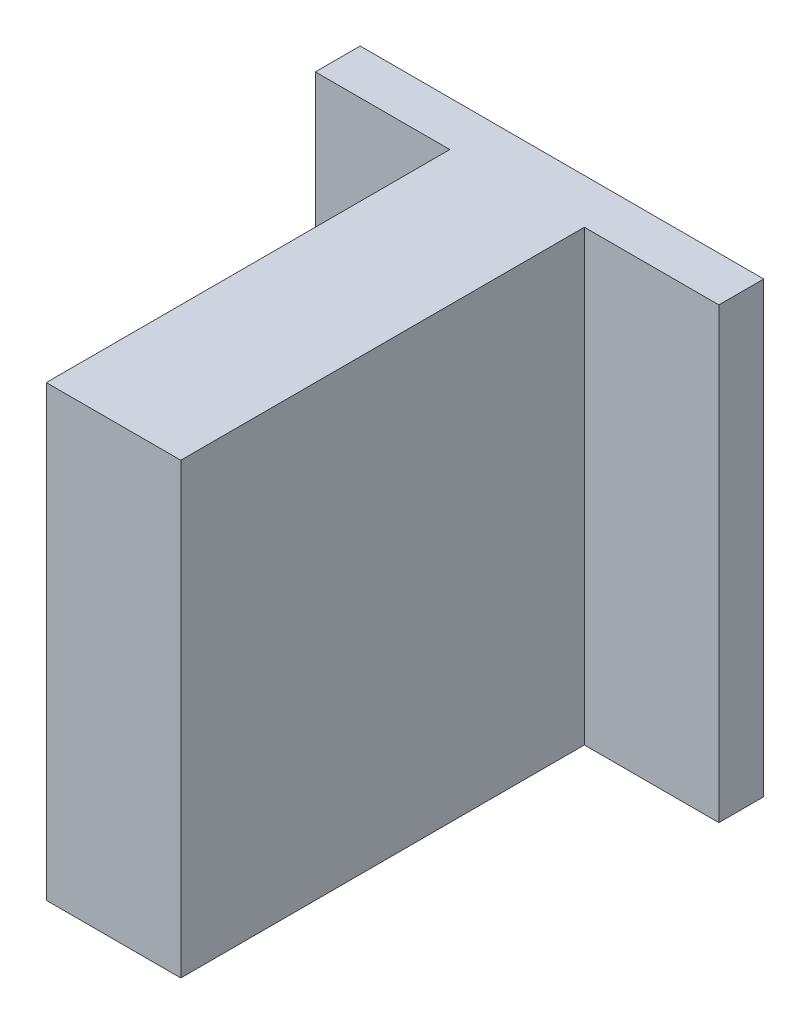
SolidWorks part; units mm, degrees
ref_plane "Front Plane" through (0, 0, 0) normal (0, 0, 1) x (1, 0, 0)
ref_plane "Top Plane" through (0, 0, 0) normal (0, 1, 0) x (1, 0, 0)
ref_plane "Right Plane" through (0, 0, 0) normal (1, 0, 0) x (0, 0, -1)
sketch "Sketch1" plane through (0, 0, 0) normal (1, 0, 0) x (0, 0, -1)
  line L1 (0, 0) -> (-25.4, 0)
  line L2 (0, 0) -> (0, 25.4)
  line L3 (0, 25.4) -> (-25.4, 25.4)
  line L4 (-25.4, 0) -> (-25.4, 25.4)
extrude "Boss-Extrude1" add sketch "Sketch1" along normal blind 3.81
sketch "Sketch2" plane through (0, 0, 0) normal (0, 0, 1) x (1, 0, 0)
  line L1 (0, 25.4) -> (-7.62, 25.4)
  line L2 (0, 25.4) -> (0, 0)
  line L3 (0, 0) -> (-7.62, 0)
  line L4 (-7.62, 25.4) -> (-7.62, 0)
extrude "Boss-Extrude2" add sketch "Sketch2" along normal blind 2.54
ref_plane "Plane2" through (3.81, 0, 0) normal (1, 0, 0) x (0, 0, -1)
mirror "Mirror2" about plane through (3.81, 0, 0) normal (1, 0, 0) of "Boss-Extrude1", "Boss-Extrude2"
